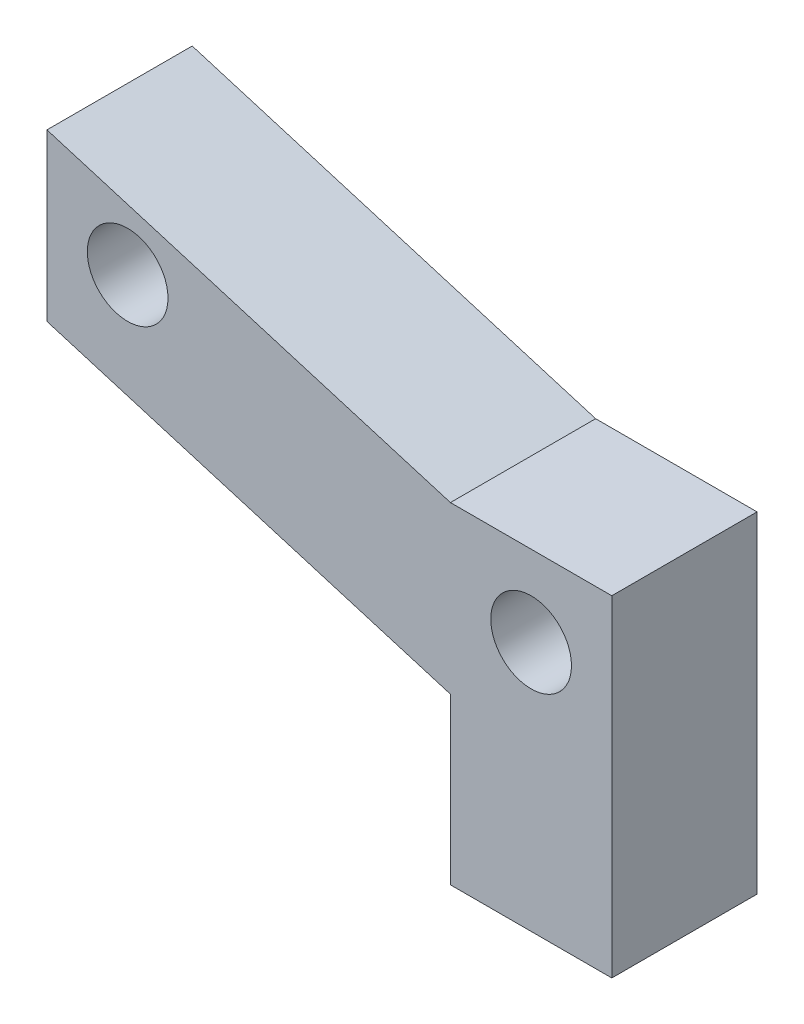
SolidWorks part; units mm, degrees
ref_plane "Front Plane" through (0, 0, 0) normal (0, 0, 1) x (1, 0, 0)
ref_plane "Top Plane" through (0, 0, 0) normal (0, 1, 0) x (1, 0, 0)
ref_plane "Right Plane" through (0, 0, 0) normal (1, 0, 0) x (0, 0, -1)
sketch "Sketch2" plane through (0, 0, 0) normal (0, 0, 1) x (1, 0, 0)
  line L0 (-15.8158, -97.1932) -> (-15.8158, -107.4744)
  line L1 (-15.8158, -97.1932) -> (9.1842, -104.6932)
  line L2 (-15.8158, -107.4744) -> (9.1842, -114.9744)
  line L8 (9.1842, -104.6932) -> (19.1842, -104.6932)
  line L9 (19.1842, -114.9744) -> (19.1842, -104.6932)
  line L12 (19.1842, -114.9744) -> (19.1842, -125.2065)
  line L13 (19.1842, -125.2065) -> (9.1842, -125.2065)
  line L14 (9.1842, -114.9744) -> (9.1842, -125.2065)
  dimension "D1" = 10
extrude "Boss-Extrude1" add sketch "Sketch2" along normal blind 9
sketch "Sketch3" plane through (0, 0, 9) normal (0, 0, 1) x (1, 0, 0)
  line L0 (14.1842, -107.1932) -> (14.1842, -104.6932) construction
  line L1 (19.1842, -104.6932) -> (9.1842, -104.6932) construction
  line L2 (16.6842, -109.6932) -> (19.1842, -109.6932) construction
  line L3 (19.1842, -125.2065) -> (19.1842, -104.6932) construction
  line L4 (-15.8158, -107.4744) -> (19.1842, -107.4744) construction
  line L5 (-13.3158, -102.4744) -> (-15.8158, -102.4744) construction
  line L6 (-15.8158, -97.1932) -> (-15.8158, -107.4744) construction
  line L7 (-10.8158, -104.9744) -> (-10.8158, -107.4744) construction
  circle A0 centre (14.1842, -109.6932) radius 2.5
  circle A1 centre (-10.8158, -102.4744) radius 2.5
  point P21 (-11.808, -103.4666)
  point P22 (-1.3537, -107.4744)
  point P23 (19.1842, -107.4744)
  dimension "D1" = 5
  dimension "D2" = 2.5
  dimension "D3" = 2.5
extrude "Cut-Extrude1" cut sketch "Sketch3" against normal blind 9
